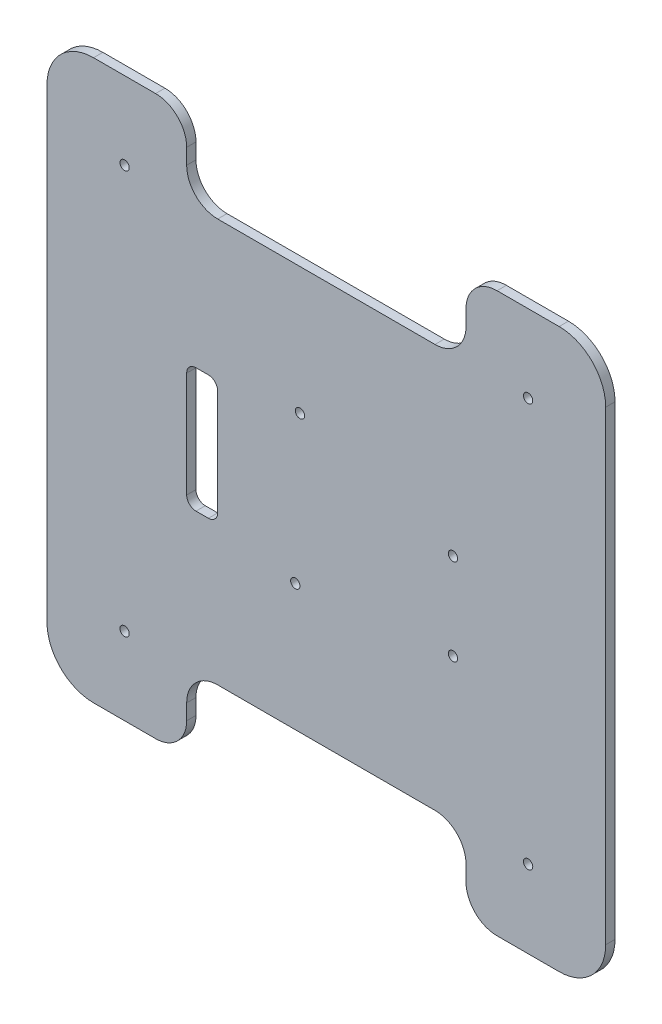
SolidWorks part; units mm, degrees
ref_plane "Front" through (0, 0, 0) normal (0, 0, 1) x (1, 0, 0)
ref_plane "Top" through (0, 0, 0) normal (0, 1, 0) x (1, 0, 0)
ref_plane "Right" through (0, 0, 0) normal (1, 0, 0) x (0, 0, -1)
sketch "Эскиз1" plane through (0, 0, 0) normal (0, 0, 1) x (1, 0, 0)
  line L1 (75, -90) -> (-75, -90)
  line L2 (90, -75) -> (90, 75)
  line L3 (75, 90) -> (-75, 90)
  line L4 (-90, -75) -> (-90, 75)
  line L5 (90, -90) -> (-90, 90) construction
  line L6 (90, 90) -> (-90, -90) construction
  arc A0 (-75, -90) -> (-90, -75) centre (-75, -75) cw
  arc A1 (75, -90) -> (90, -75) centre (75, -75) ccw
  arc A2 (90, 75) -> (75, 90) centre (75, 75) ccw
  arc A3 (-90, 75) -> (-75, 90) centre (-75, 75) cw
  point P0 (0, 0)
  dimension "D3" = 15
  dimension "D1" = 180
  dimension "D2" = 180
extrude "Бобышка-Вытянуть1" add sketch "Эскиз1" along normal blind 3
hole_wizard "Диаметр отверстия Ø3.0 (3)1" positions "Эскиз5" profile "Эскиз4" hole size "Ø3.0" standard "Ansi Metric" end condition up to next
sketch "Эскиз5" plane through (0, 0, 3) normal (0, 0, 1) x (1, 0, 0)
  line L4 (-90, 0) -> (-10, 0) construction
  line L5 (-90, 75) -> (-90, -75) construction
  line L6 (-10, 0) -> (40.8, 0) construction
  line L7 (40.8, 0) -> (90, 0) construction
  line L8 (90, -75) -> (90, 75) construction
  line L10 (-10, -26.65) -> (-10, 26.65) construction
  line L12 (40.8, -19.05) -> (40.8, 8.85) construction
  line L13 (-10, 24.05) -> (-8.5, 24.05) construction
  point P33 (-10, -24.15)
  point P45 (40.8, 8.85)
  point P48 (40.8, -19.05)
  point P59 (-8.5, 24.05)
  dimension "D1" = 53.3
  dimension "D2" = 50.8
  dimension "D3" = 27.9
  dimension "D4" = 2.5
  dimension "D5" = 5.1
  dimension "D6" = 1.5
  dimension "D7" = 80
  dimension "D8" = 15.2
sketch "Эскиз4" plane through (-10, -24.15, 3) normal (1, 0, 0) x (0, -1, 0)
  line L0 (0, 0) -> (0, 3)
  line L1 (0, 3) -> (1.5, 3)
  line L2 (1.5, 3) -> (1.5, 0)
  line L5 (1.5, 0) -> (0, 0)
  line L11 (0, -6.35) -> (0, 107.95) construction
  dimension "Диаметр сквозного отверстия" = 3
  dimension "Глубина сквозного отверстия" = 3
sketch "Эскиз7" plane through (0, 0, 3) normal (0, 0, 1) x (1, 0, 0)
  line L0 (0, -90) -> (0, 90) construction
  line L1 (-75, -90) -> (75, -90) construction
  line L2 (75, 90) -> (-75, 90) construction
  line L4 (45, 65) -> (-45, 65)
  line L5 (45, 65) -> (45, 90)
  line L6 (45, 90) -> (-45, 90)
  line L7 (-45, 65) -> (-45, 90)
  line L8 (45, 65) -> (-45, 90) construction
  line L9 (45, 90) -> (-45, 65) construction
  line L10 (45, -65) -> (-45, -65)
  line L11 (45, -65) -> (45, -90)
  line L12 (45, -90) -> (-45, -90)
  line L13 (-45, -65) -> (-45, -90)
  line L14 (45, -65) -> (-45, -90) construction
  line L15 (45, -90) -> (-45, -65) construction
  point P6 (0, 77.5)
  point P11 (0, -77.5)
  dimension "D1" = 90
  dimension "D2" = 25
extrude "Вырез-Вытянуть1" cut sketch "Эскиз7" against normal through all
fillet "Скругление7" radius 10 8 edges at (45, -90, 1.5) (45, -65, 1.5) (-45, -65, 1.5) (-45, -90, 1.5) (45, 65, 1.5) (45, 90, 1.5) (-45, 90, 1.5) (-45, 65, 1.5)
hole_wizard "Диаметр отверстия Ø3.0 (3)2" positions "Эскиз9" profile "Эскиз8" hole size "Ø3.0" standard "Ansi Metric" end condition up to next
sketch "Эскиз9" plane through (0, 0, 3) normal (0, 0, 1) x (1, 0, 0)
  line L8 (65, -90) -> (65, -65) construction
  line L9 (55, -90) -> (75, -90) construction
  line L10 (65, -65) -> (65, 65) construction
  line L11 (65, 65) -> (65, 90) construction
  line L12 (75, 90) -> (55, 90) construction
  line L14 (-65, 90) -> (-65, 65) construction
  line L15 (-55, 90) -> (-75, 90) construction
  line L16 (-65, 65) -> (-65, -65) construction
  line L17 (-65, -65) -> (-65, -90) construction
  line L18 (-75, -90) -> (-55, -90) construction
  line L20 (-65, -65) -> (-90, -65) construction
  line L21 (-90, 75) -> (-90, -75) construction
  point P50 (-65, -65)
  point P53 (65, -65)
  point P56 (65, 65)
  point P61 (-65, 65)
sketch "Эскиз8" plane through (-65, -65, 3) normal (1, 0, 0) x (0, -1, 0)
  line L0 (0, 0) -> (0, 3)
  line L1 (0, 3) -> (1.5, 3)
  line L2 (1.5, 3) -> (1.5, 0)
  line L5 (1.5, 0) -> (0, 0)
  line L11 (0, -6.35) -> (0, 107.95) construction
  dimension "Диаметр сквозного отверстия" = 3
  dimension "Глубина сквозного отверстия" = 3
sketch "Sketch1" plane through (0, 0, 3) normal (0, 0, 1) x (1, 0, 0)
  line L0 (-40, 0) -> (0, 0) construction
  line L1 (-45, -20) -> (-35, -20)
  line L2 (-45, -20) -> (-45, 20)
  line L3 (-45, 20) -> (-35, 20)
  line L4 (-35, -20) -> (-35, 20)
  line L5 (-45, -20) -> (-35, 20) construction
  line L6 (-45, 20) -> (-35, -20) construction
  point P0 (-40, 0)
  dimension "D1" = 10
  dimension "D2" = 40
  dimension "D3" = 40
extrude "Cut-Extrude1" cut sketch "Sketch1" against normal through all
fillet "Fillet1" radius 3 4 edges at (-35, 20, 1.5) (-45, 20, 1.5) (-45, -20, 1.5) (-35, -20, 1.5)
